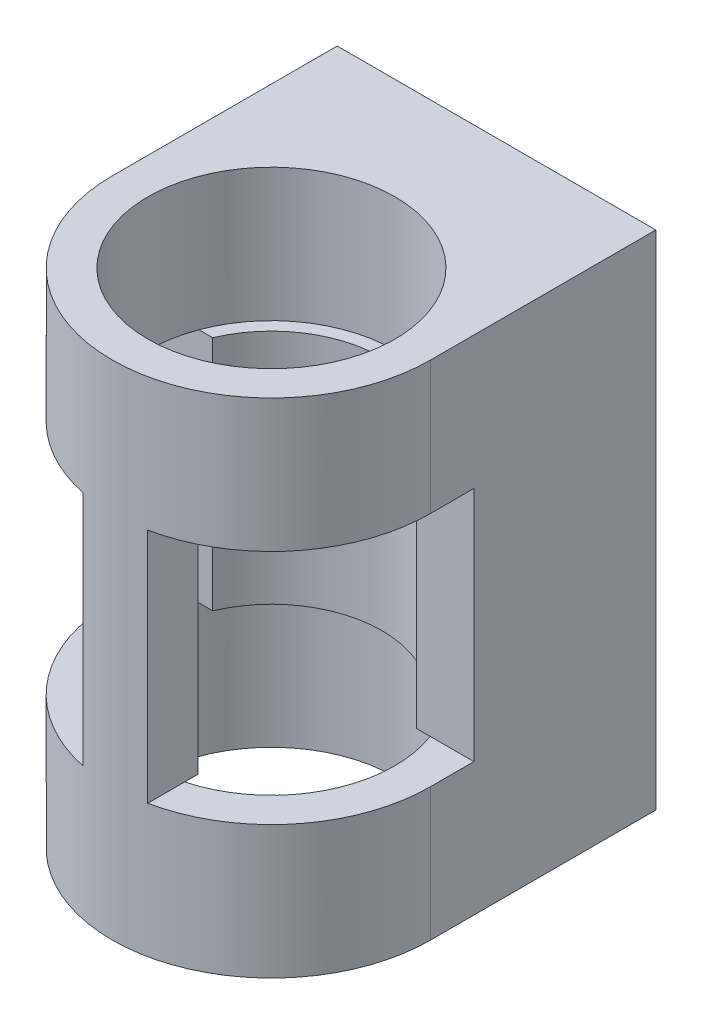
SolidWorks part; units mm, degrees
material "6061-T6 (SS)"
ref_plane "Front Plane" through (0, 0, 0) normal (0, 0, 1) x (1, 0, 0)
ref_plane "Top Plane" through (0, 0, 0) normal (0, 1, 0) x (1, 0, 0)
ref_plane "Right Plane" through (0, 0, 0) normal (1, 0, 0) x (0, 0, -1)
sketch "Sketch1" plane through (0, 0, 0) normal (0, 1, 0) x (1, 0, 0)
  line L0 (-13.3188, 0) -> (-13.3188, 13.3188)
  line L2 (13.3188, 13.3188) -> (13.3188, 0)
  line L3 (-13.3188, 13.3188) -> (-13.3188, 17.8188)
  line L5 (13.3188, 17.8188) -> (13.3188, 13.3188)
  line L6 (-13.3188, 17.8188) -> (-13.3188, 18.8188)
  line L7 (-13.3188, 18.8188) -> (13.3188, 18.8188)
  line L8 (13.3188, 18.8188) -> (13.3188, 17.8188)
  arc A1 (-13.3188, 0) -> (13.3188, 0) centre (0, 0) ccw
  circle A3 centre (0, 0) radius 9.25
extrude "Boss-Extrude1" add sketch "Sketch1" along normal blind 42
sketch "Sketch2" plane through (0, 42, 0) normal (0, 1, 0) x (1, 0, 0)
  circle A0 centre (0, 0) radius 10.3187
  dimension "D1" = 20.6375
extrude "Cut-Extrude1" cut sketch "Sketch2" against normal blind 11.1125
sketch "Sketch3" plane through (0, 0, 0) normal (0, -1, 0) x (1, 0, 0)
  circle A0 centre (0, 0) radius 10.3175
  dimension "D1" = 20.635
extrude "Cut-Extrude2" cut sketch "Sketch3" against normal blind 11.1125
ref_plane "Plane1" through (0, 30.8875, 0) normal (0, 1, 0) x (1, 0, 0)
sketch "Sketch4" plane through (0, 30.8875, 0) normal (0, 1, 0) x (1, 0, 0)
  line L0 (2.7021, -6.2037) -> (-2.7021, -6.2037)
  line L1 (-2.7021, -6.2037) -> (-2.7021, -16.0819)
  line L2 (-2.7021, -16.0819) -> (-18.9578, -16.0819)
  line L3 (-18.9578, -16.0819) -> (-18.9578, 3.6069)
  line L4 (-18.9578, 3.6069) -> (22.5045, 3.6069)
  line L5 (22.5045, 3.6069) -> (22.5045, -16.0819)
  line L6 (22.5045, -16.0819) -> (2.7021, -16.0819)
  line L7 (2.7021, -16.0819) -> (2.7021, -6.2037)
  point P3 (0, -6.2037)
extrude "Cut-Extrude3" cut sketch "Sketch4" against normal up to surface (19.775 mm away) up to face at (0, 11.1125, -9.25)
sketch "Sketch5" plane through (0, 0, -18.8188) normal (0, 0, -1) x (-1, 0, 0)
  line L0 (-13.3188, 42) -> (-7.8188, 42) construction
  line L1 (-13.3188, 42) -> (13.3188, 42) construction
  line L2 (-7.8188, 42) -> (-7.8188, 36.5) construction
  line L3 (13.3188, 42) -> (7.8188, 42) construction
  line L4 (7.8188, 42) -> (7.8188, 36.5) construction
  line L5 (13.3188, 0) -> (7.8188, 0) construction
  line L6 (-13.3188, 0) -> (13.3188, 0) construction
  line L7 (7.8188, 0) -> (7.8188, 5.5) construction
  line L8 (-13.3188, 0) -> (-7.8188, 0) construction
  line L9 (-7.8188, 0) -> (-7.8188, 5.5) construction
  circle A0 centre (-7.8188, 5.5) radius 3
  circle A1 centre (7.8188, 5.5) radius 3
  circle A2 centre (7.8188, 36.5) radius 3
  circle A3 centre (-7.8188, 36.5) radius 3
extrude "Cut-Extrude4" cut sketch "Sketch5" against normal blind 8
sketch "Sketch6" plane through (0, 0, -18.8188) normal (0, 0, -1) x (-1, 0, 0)
  line L0 (0, 0) -> (0, 42) construction
  line L1 (-13.3188, 42) -> (13.3188, 42) construction
  line L4 (-9.5, 11) -> (9.5, 11)
  line L5 (-9.5, 11) -> (-9.5, 31)
  line L6 (-9.5, 31) -> (9.5, 31)
  line L7 (9.5, 11) -> (9.5, 31)
  line L8 (-9.5, 11) -> (9.5, 31) construction
  line L9 (-9.5, 31) -> (9.5, 11) construction
  point P5 (0, 21)
extrude "Cut-Extrude5" cut sketch "Sketch6" against normal blind 6
fillet "Fillet1" radius 2.38 4 edges at (9.5, 31, -15.8188) (-9.5, 31, -15.8188) (9.5, 11, -15.8188) (-9.5, 11, -15.8188)
